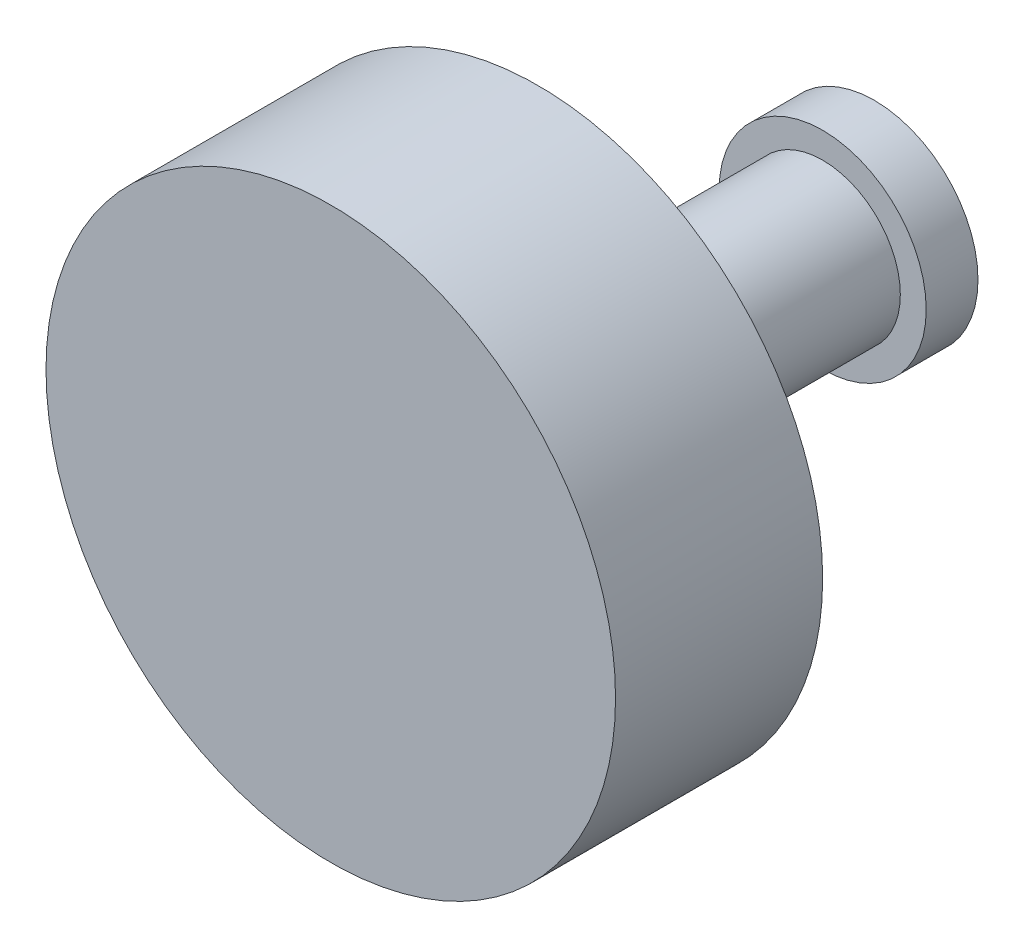
SolidWorks part; units mm, degrees
ref_plane "前视基准面" through (0, 0, 0) normal (0, 0, 1) x (1, 0, 0)
ref_plane "上视基准面" through (0, 0, 0) normal (0, 1, 0) x (1, 0, 0)
ref_plane "右视基准面" through (0, 0, 0) normal (1, 0, 0) x (0, 0, -1)
sketch "草图1" plane through (0, 0, 0) normal (0, 0, 1) x (1, 0, 0)
  circle A0 centre (0, 0) radius 110
  dimension "D1" = 220
extrude "凸台-拉伸1" add sketch "草图1" along normal blind 80
sketch "草图2" plane through (0, 0, 0) normal (0, 0, -1) x (-1, 0, 0)
  circle A0 centre (0, 0) radius 30
extrude "凸台-拉伸2" add sketch "草图2" along normal blind 110
sketch "草图3" plane through (0, 0, -110) normal (0, 0, -1) x (-1, 0, 0)
  circle A0 centre (0, 0) radius 40
extrude "凸台-拉伸3" add sketch "草图3" along normal blind 20
scale "缩放比例1" scale about origin uniform scaling yes scale factor 0.345
